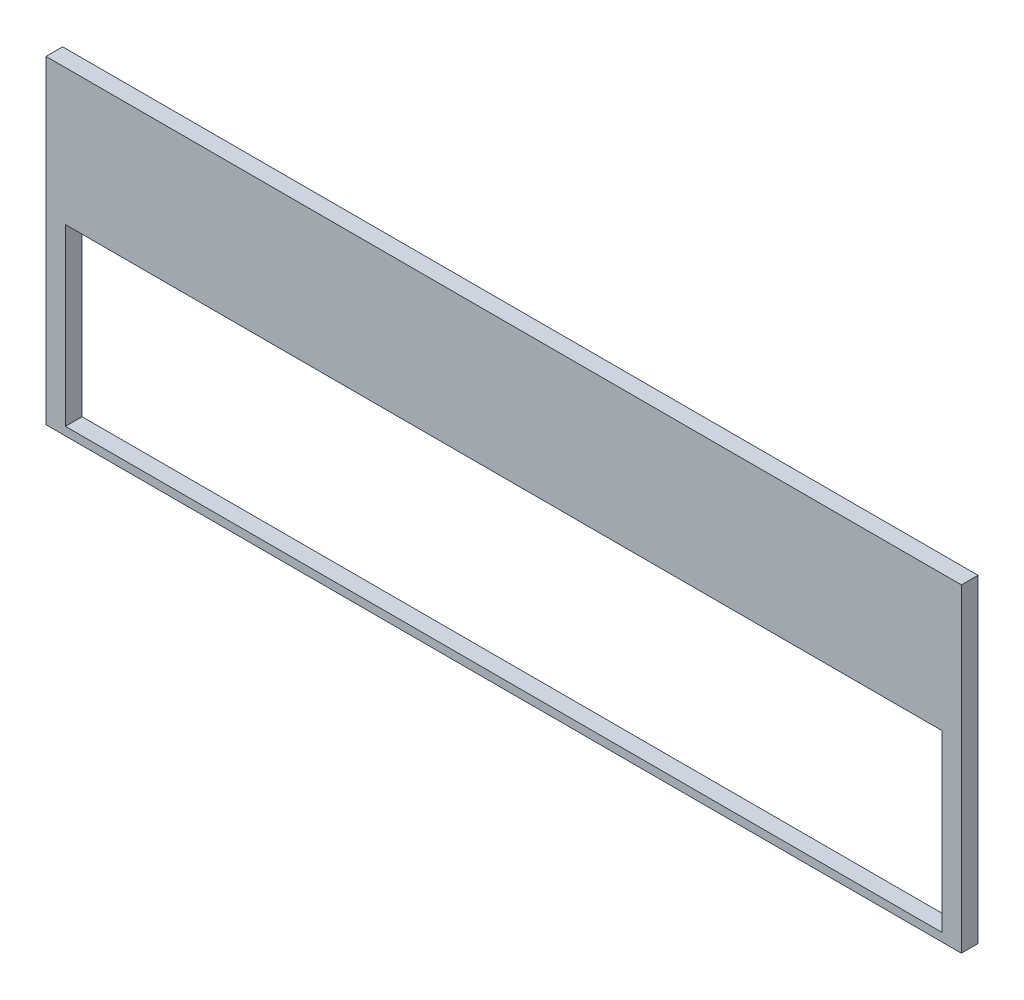
SolidWorks part; units mm, degrees
ref_plane "Plan de face" through (0, 0, 0) normal (0, 0, 1) x (1, 0, 0)
ref_plane "Plan de dessus" through (0, 0, 0) normal (0, 1, 0) x (1, 0, 0)
ref_plane "Plan de droite" through (0, 0, 0) normal (1, 0, 0) x (0, 0, -1)
sketch "Esquisse1" plane through (0, 0, 0) normal (0, 0, 1) x (1, 0, 0)
  line L0 (0, 57.5) -> (0, -57.5) construction
  line L1 (165, -57.5) -> (-165, -57.5)
  line L2 (165, -57.5) -> (165, 57.5)
  line L3 (165, 57.5) -> (-165, 57.5)
  line L4 (-165, -57.5) -> (-165, 57.5)
  line L5 (-165, 0) -> (165, 0) construction
  point P0 (0, 0)
  dimension "D1" = 115
  dimension "D2" = 330
extrude "Boss.-Extru.1" add sketch "Esquisse1" along normal blind 6
sketch "Esquisse2" plane through (0, 0, 0) normal (0, 0, -1) x (-1, 0, 0)
  line L0 (-165, -57.5) -> (-165, 57.5) construction
  line L1 (-158, -54.5) -> (158, -54.5)
  line L2 (-158, -54.5) -> (-158, 8.5)
  line L3 (-158, 8.5) -> (158, 8.5)
  line L4 (158, -54.5) -> (158, 8.5)
  line L5 (165, -57.5) -> (-165, -57.5) construction
  line L6 (165, 57.5) -> (165, -57.5) construction
  dimension "D1" = 63
  dimension "D2" = 7
  dimension "D3" = 3
  dimension "D4" = 7
extrude "Enlèv. mat.-Extru.1" cut sketch "Esquisse2" against normal through all
